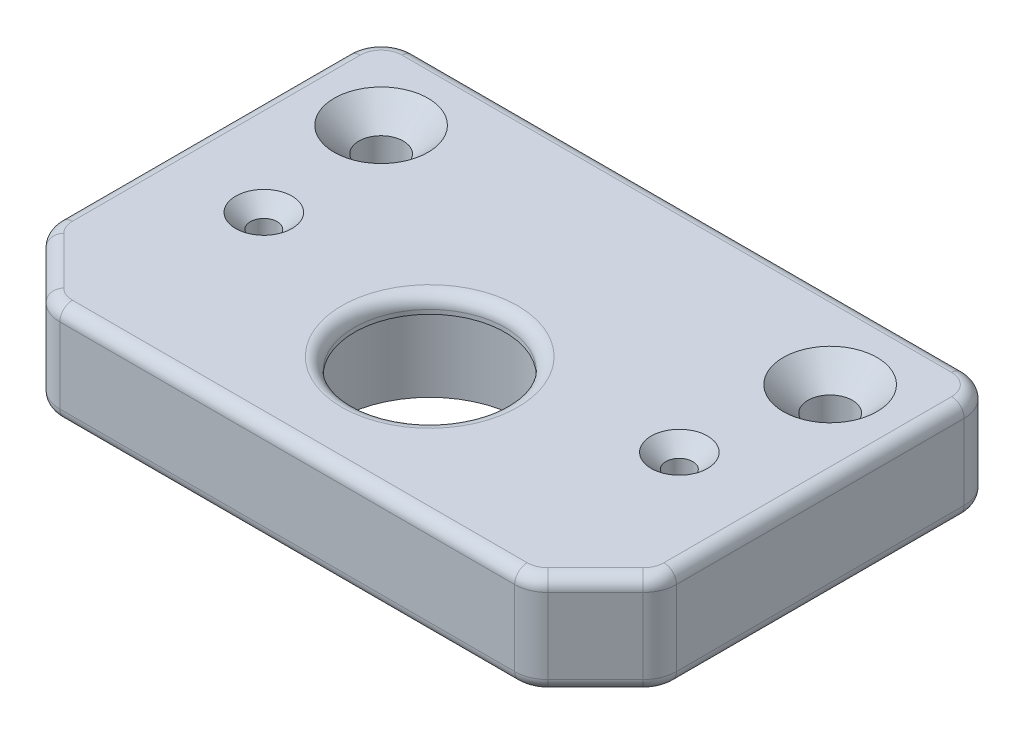
SolidWorks part; units mm, degrees
ref_plane "Front Plane" through (0, 0, 0) normal (0, 0, 1) x (1, 0, 0)
ref_plane "Top Plane" through (0, 0, 0) normal (0, 1, 0) x (1, 0, 0)
ref_plane "Right Plane" through (0, 0, 0) normal (1, 0, 0) x (0, 0, -1)
sketch "Sketch3" plane through (0, 0, 0) normal (0, 1, 0) x (1, 0, 0)
  line L0 (0, 11) -> (-17, 11) construction
  line L1 (0, 11) -> (-61.044, 11) construction
  line L2 (-17, -17) -> (17, -17)
  line L3 (17, -17) -> (17, 11) construction
  line L4 (-17, -17) -> (-17, 11) construction
  line L5 (-36.8, 11) -> (-17, 11) construction
  line L6 (-11, 11) -> (-17, 11) construction
  line L7 (-17, 11) -> (-11, 11) construction
  line L8 (11, 11) -> (17, 11) construction
  line L9 (-17, 11) -> (-11, 11) construction
  line L10 (-36.8, 11) -> (-36.8, -17)
  line L11 (-36.8, -17) -> (-17, -17)
  line L12 (36.8, 11) -> (36.8, -17)
  line L13 (36.8, -17) -> (17, -17)
  line L14 (-36.8, 11) -> (-36.8, 31)
  line L15 (-36.8, 31) -> (36.8, 31)
  line L16 (36.8, 11) -> (36.8, 31)
  line L17 (0, 11) -> (36.8, 11)
  line L18 (-11, 11) -> (0, 11) construction
  line L19 (11, 11) -> (36.8, 11)
  line L20 (0, 11) -> (11, 11) construction
  line L21 (-11, 11) -> (0, 11) construction
  line L22 (-36.8, 11) -> (-17, 11) construction
  line L23 (-36.8, 11) -> (-73.5856, 11) construction
  line L24 (-17, 11) -> (-36.8, 11) construction
  circle A0 centre (0, 0) radius 11 construction
  circle A1 centre (0, 0) radius 11
  point P7 (0, -11)
  point P8 (11, 0)
  point P11 (-11, 0)
  point P13 (0, 11)
  point P18 (0, 11)
  point P23 (0, 11)
  dimension "D1" = 22
  dimension "D2" = 48
  dimension "D5" = 73.6
  dimension "D6" = 20
extrude "Boss-Extrude1" add sketch "Sketch3" along normal blind 10
sketch "Sketch4" plane through (0, 10, 0) normal (0, 1, 0) x (1, 0, 0)
  line L1 (-36.8, 31) -> (36.8, 31)
  line L2 (-36.8, 31) -> (-36.8, -17)
  line L3 (-36.8, -17) -> (36.8, -17)
  line L4 (36.8, 31) -> (36.8, -17)
  circle A0 centre (0, 0) radius 9
  dimension "D1" = 18
extrude "Boss-Extrude2" add sketch "Sketch4" along normal blind 2
sketch "Sketch5" plane through (0, 12, 0) normal (0, 1, 0) x (1, 0, 0)
  line L0 (36.8, -17) -> (36.8, 31) construction
  line L1 (-36.8, 31) -> (36.8, 31) construction
  line L2 (-36.8, 31) -> (-36.8, 11) construction
  line L3 (-36.8, 11) -> (36.8, 11) construction
  line L4 (36.8, 31) -> (36.8, 11) construction
  line L5 (-36.8, 21) -> (36.8, 21) construction
  line L6 (0, 11) -> (0, 31) construction
  line L7 (-36.8, 31) -> (-36.8, -17) construction
  point P11 (-26.8, 21)
  point P12 (26.8, 21)
  point P13 (24.8, 5)
  point P14 (-24.8, 5)
  dimension "D1" = 20
  dimension "D2" = 10
  dimension "D3" = 10
  dimension "D4" = 6
  dimension "D5" = 6
  dimension "D6" = 12
  dimension "D7" = 12
hole_wizard "CSK for M5 SFHCS1" positions "Sketch5" profile "Sketch6" countersink size "M5" standard "ANSI Metric"
sketch "Sketch6" plane through (26.8, 12, -21) normal (1, 0, 0) x (0, 0, 1)
  line L0 (0, 0) -> (0, 12)
  line L1 (0, 12) -> (2.65, 12)
  line L2 (2.65, 12) -> (2.65, 2.95)
  line L3 (2.65, 2.95) -> (5.6, 0)
  line L5 (5.6, 0) -> (0, 0)
  line L6 (-2.65, 2.95) -> (-5.6, 0) construction
  line L11 (0, -6.35) -> (0, 107.95) construction
  dimension "Thru Hole Dia." = 5.3
  dimension "Thru Hole Depth" = 12
  dimension "Near C'Sink Dia." = 11.2
  dimension "Near C'Sink Angle" = 90
chamfer "Chamfer1" distance 8 angle 45 2 edges at (-36.8, 6, 17) (36.8, 6, 17)
fillet "Fillet1" radius 4 6 edges at (-36.8, 6, -31) (36.8, 6, -31) (36.8, 6, 9) (28.8, 6, 17) (-36.8, 6, 9) (-28.8, 6, 17)
fillet "Fillet2" radius 1.5 25 edges at (-28.6739, 0, 16.6955) (0, 0, 17) (28.6739, 0, 16.6955) (32.8, 0, 13) (36.4955, 0, 8.8739) (36.8, 0, -9.8284) (35.6284, 0, -29.8284) (0, 0, -31) (-35.6284, 0, -29.8284) (-36.8, 0, -9.8284) (-36.4955, 0, 8.8739) (-36.4955, 12, 8.8739) (-36.8, 12, -9.8284) (-35.6284, 12, -29.8284) (0, 12, -31) (35.6284, 12, -29.8284) (36.8, 12, -9.8284) (36.4955, 12, 8.8739) (32.8, 12, 13) (28.6739, 12, 16.6955) (0, 12, 17) (-28.6739, 12, 16.6955) (-32.8, 0, 13) (-32.8, 12, 13) (0, 12, 9)
sketch "Sketch7" plane through (0, 12, 0) normal (0, 1, 0) x (1, 0, 0)
  point P0 (24.8, 5)
  point P2 (-24.8, 5)
hole_wizard "CSK for M3 SFHCS1" positions "Sketch7" profile "Sketch8" countersink size "M3" standard "ANSI Metric" end condition through all
sketch "Sketch8" plane through (24.8, 12, -5) normal (1, 0, 0) x (0, 0, 1)
  line L0 (0, 0) -> (0, 12)
  line L1 (0, 12) -> (1.6, 12)
  line L2 (1.6, 12) -> (1.6, 1.76)
  line L3 (1.6, 1.76) -> (3.36, 0)
  line L5 (3.36, 0) -> (0, 0)
  line L6 (-1.6, 1.76) -> (-3.36, 0) construction
  line L11 (0, -6.35) -> (0, 107.95) construction
  dimension "Thru Hole Dia." = 3.2
  dimension "Thru Hole Depth" = 12
  dimension "Near C'Sink Dia." = 6.72
  dimension "Near C'Sink Angle" = 90
